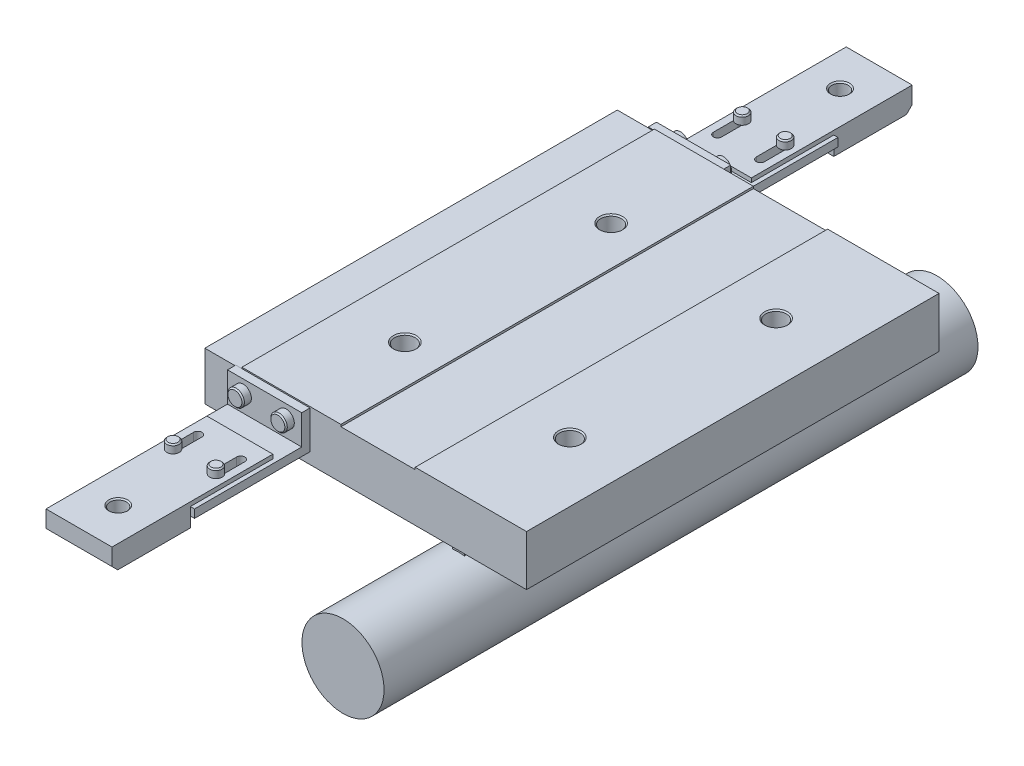
SolidWorks part; units mm, degrees
material "6061-O (SS)"
ref_plane "Plane1" through (0, 0, 0) normal (0, 0, 1) x (1, 0, 0)
ref_plane "Plane2" through (0, 0, 0) normal (0, 1, 0) x (1, 0, 0)
ref_plane "Plane3" through (0, 0, 0) normal (1, 0, 0) x (0, 0, -1)
sketch "Sketch1" plane through (0, 0, 0) normal (0, 0, 1) x (1, 0, 0)
  line L0 (0, 0) -> (0, 8.6799) construction
  line L1 (-22.5, 6.1) -> (22.5, 6.1)
  line L2 (-22.5, 6.1) -> (-22.5, -6.1)
  line L3 (-22.5, -6.1) -> (22.5, -6.1)
  line L4 (22.5, 6.1) -> (22.5, -6.1)
  line L5 (0, 0) -> (8.2602, 0) construction
  dimension "NW" = 45
  dimension "D2" = 12.2
extrude "Base-Extrude" add sketch "Sketch1" along normal mid plane 100
sketch "Sketch16" plane through (0, 6.1, 0) normal (0, 1, 0) x (-1, 0, 0)
  line L0 (22.5, 50) -> (22.5, -50) construction
  line L1 (22.5, -50) -> (55.5, -50)
  line L2 (22.5, -50) -> (22.5, 50)
  line L3 (22.5, 50) -> (55.5, 50)
  line L4 (55.5, -50) -> (55.5, 50)
  line L5 (-22.5, -50) -> (22.5, -50) construction
  line L6 (-22.5, 50) -> (22.5, 50) construction
  line L7 (-22.5, 50) -> (-22.5, -50) construction
  dimension "LW" = 78
extrude "Table_Extension" add sketch "Sketch16" against normal up to surface (12.2 mm away) up to face at (0, -6.1, 0)
sketch "Sketch3" plane through (0, 6.1, 0) normal (0, 1, 0) x (-1, 0, 0)
  line L0 (-1.7132, 0) -> (53.4775, 0) construction
  line L2 (-22.5, 50) -> (-22.5, -50) construction
  circle A0 centre (32, -25) radius 2.5
  circle A1 centre (-8, -25) radius 2.5
  circle A2 centre (32, 25) radius 2.5
  circle A3 centre (-8, 25) radius 2.5
  dimension "MM" = 5
  dimension "PA" = 50
  dimension "PB" = 40
  dimension "PC" = 14.5
extrude "MountHoles" cut sketch "Sketch3" against normal blind 8
sketch "Sketch14" plane through (0, 0, 0) normal (0, 0, 1) x (1, 0, 0)
  line L1 (1.45, 6.1) -> (-1.45, 6.1)
  line L2 (0, 0) -> (0, -12.7939) construction
  line L3 (-1.45, 6.1) -> (-1.45, -22.4)
  line L4 (1.45, 6.1) -> (1.45, -22.4)
  line L5 (-1.45, -22.4) -> (1.45, -22.4)
  line L7 (22.5, 6.1) -> (-55.5, 6.1) construction
  dimension "D1" = 2.9
  dimension "D2" = 28.5
extrude "Connection" add sketch "Sketch14" along normal mid plane 88
sketch "Sketch15" plane through (0, 0, 0) normal (0, 0, 1) x (1, 0, 0)
  line L0 (-1.45, -22.4) -> (1.45, -22.4) construction
  circle A0 centre (0, -22.4) radius 9.95
  dimension "D1" = 19.9
extrude "Piston" add sketch "Sketch15" along normal mid plane 144
sketch "Sketch17" plane through (0, 0, 50) normal (0, 0, 1) x (1, 0, 0)
  line L0 (22.5, 6.1) -> (-55.5, 6.1) construction
  line L1 (-55.5, 6.1) -> (-46.5, 6.1)
  line L2 (-55.5, 6.1) -> (-55.5, 5.6)
  line L3 (-55.5, 5.6) -> (-46.5, 5.6)
  line L4 (-46.5, 6.1) -> (-46.5, 5.6)
  line L5 (-22.5, 6.1) -> (-4.5, 6.1)
  line L6 (-22.5, 6.1) -> (-22.5, 5.6)
  line L7 (-22.5, 5.6) -> (-4.5, 5.6)
  line L8 (-4.5, 6.1) -> (-4.5, 5.6)
  dimension "D1" = 18
  dimension "D2" = 9
  dimension "D3" = 0.5
  dimension "D4" = 24
extrude "Grooves" cut sketch "Sketch17" against normal through all
ref_plane "EndLockPlane" through (-39, 0, 0) normal (1, 0, 0) x (0, 0, -1)
sketch "Sketch18" plane through (-39, 0, 0) normal (1, 0, 0) x (0, 0, -1)
  line L0 (-50, 5.8) -> (-52, 5.8)
  line L1 (-50, -6.1) -> (-50, 6.1) construction
  line L2 (-52, 5.8) -> (-52, -1.4)
  line L3 (-52, -1.4) -> (-78, -1.4)
  line L4 (-78, -1.4) -> (-78, -3.4)
  line L5 (-78, -3.4) -> (-50, -3.4)
  line L6 (-50, -3.4) -> (-50, 5.8)
  line L7 (-50, 6.1) -> (50, 6.1) construction
  dimension "D1" = 28
  dimension "D2" = 2
  dimension "D3" = 9.2
  dimension "H-H1" = 0.3
extrude "EndLockPlate1" add sketch "Sketch18" along normal mid plane 18
sketch "Sketch19" plane through (-39, 0, 0) normal (1, 0, 0) x (0, 0, -1)
  line L0 (-58, -1.4) -> (-58, -0.4)
  line L1 (-52, -1.4) -> (-78, -1.4) construction
  line L2 (-58, -0.4) -> (-97, -0.4)
  line L3 (-97, -0.4) -> (-97, -4.5)
  line L4 (-97, -4.5) -> (-95.6, -5.9)
  line L5 (-95.6, -5.9) -> (-78, -5.9)
  line L6 (-78, -5.9) -> (-78, -1.4)
  line L7 (-78, -1.4) -> (-58, -1.4)
  line L8 (-50, -6.1) -> (-50, 6.1) construction
  line L9 (-50, 5.8) -> (-52, 5.8) construction
  line L10 (-78, -1.4) -> (-78, -3.4) construction
  dimension "D1" = 45
  dimension "LL-L1" = 47
  dimension "H2-NE" = 5.5
  dimension "H1-H2" = 6.2
  dimension "D2" = 39
  dimension "D3" = 1.4
extrude "EndLockPlate2" add sketch "Sketch19" along normal mid plane 16
sketch "Sketch20" plane through (0, -0.4, 0) normal (0, 1, 0) x (-1, 0, 0)
  line L0 (39, 0) -> (39, 88.447) construction
  line L1 (39, 50) -> (39, -50) construction
  line L2 (32.8, 63) -> (32.8, 69)
  line L3 (34.8, 69) -> (34.8, 63)
  line L4 (31, 97) -> (47, 97) construction
  line L6 (43.2, 69) -> (43.2, 63)
  line L7 (45.2, 63) -> (45.2, 69)
  circle A0 centre (39, 87.5) radius 2
  arc A1 (32.8, 69) -> (34.8, 69) centre (33.8, 69) cw
  arc A2 (34.8, 63) -> (32.8, 63) centre (33.8, 63) cw
  arc A3 (43.2, 63) -> (45.2, 63) centre (44.2, 63) ccw
  arc A4 (45.2, 69) -> (43.2, 69) centre (44.2, 69) ccw
  dimension "D1" = 18.5
  dimension "D2" = 9.5
  dimension "D3" = 1
  dimension "D4" = 4
  dimension "TL" = 6
  dimension "W3" = 10.4
extrude "EndLockHoles" cut sketch "Sketch20" against normal through all
sketch "Sketch21" plane through (0, -0.4, 0) normal (0, 1, 0) x (-1, 0, 0)
  circle A0 centre (44.2, 69) radius 1.5
  circle A1 centre (33.8, 69) radius 1.5
  dimension "D1" = 3
extrude "EndLockAdjustScrews" add sketch "Sketch21" along normal blind 2
sketch "Sketch23" plane through (0, 0, 52) normal (0, 0, 1) x (1, 0, 0)
  line L0 (-39, -0.4) -> (-39, 8.772) construction
  line L1 (-31, -0.4) -> (-47, -0.4) construction
  line L2 (-30, 5.8) -> (-48, 5.8) construction
  circle A0 centre (-44.2, 2.7) radius 2
  circle A1 centre (-33.8, 2.7) radius 2
  dimension "D1" = 4
  dimension "D2" = 10.4
  dimension "D3" = 3.1
extrude "EndLockMountScrews" add sketch "Sketch23" along normal blind 2
mirror "EndLockMirror" about plane through (0, 0, 0) normal (0, 0, 1) of "EndLockMountScrews", "EndLockAdjustScrews", "EndLockHoles", "EndLockPlate2", "EndLockPlate1"
chamfer "Chamfer1" distance 0.3 angle 45 12 edges at (-32, 6.1, -22.5) (8, 6.1, -27.5) (8, 6.1, 27.5) (-32, 6.1, 22.5) (-44.2, 1.6, -70.5) (-33.8, 1.6, -70.5) (-39, -0.4, -89.5) (-39, -0.4, 89.5) (-35.8, 2.7, 54) (-42.2, 2.7, 54) (-33.8, 1.6, 70.5) (-44.2, 1.6, 70.5)
